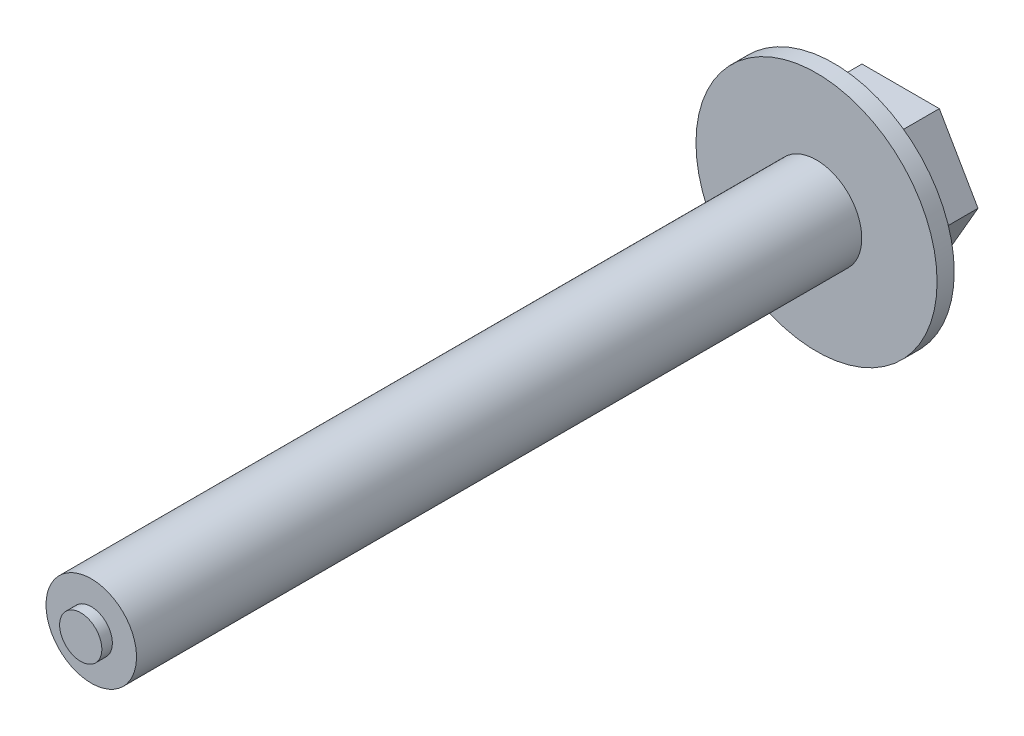
SolidWorks part; units mm, degrees
material "Ti-6Al-4VSolution treated and aged (SS)"
ref_plane "Front Plane" through (0, 0, 0) normal (0, 0, 1) x (1, 0, 0)
ref_plane "Top Plane" through (0, 0, 0) normal (0, 1, 0) x (1, 0, 0)
ref_plane "Right Plane" through (0, 0, 0) normal (1, 0, 0) x (0, 0, -1)
sketch "Sketch1" plane through (0, 0, 0) normal (0, 0, 1) x (1, 0, 0)
  line L1 (3.6662, 0) -> (1.8331, 3.175)
  line L2 (1.8331, 3.175) -> (-1.8331, 3.175)
  line L3 (-1.8331, 3.175) -> (-3.6662, 0)
  line L4 (-3.6662, 0) -> (-1.8331, -3.175)
  line L5 (-1.8331, -3.175) -> (1.8331, -3.175)
  line L6 (1.8331, -3.175) -> (3.6662, 0)
  circle A0 centre (0, 0) radius 3.175 construction
  dimension "D1" = 6.35
extrude "Boss-Extrude1" add sketch "Sketch1" along normal blind 3.175
sketch "Sketch2" plane through (0, 0, 3.175) normal (0, 0, 1) x (1, 0, 0)
  circle A0 centre (0, 0) radius 5.715
  dimension "D1" = 11.43
extrude "Boss-Extrude2" add sketch "Sketch2" along normal blind 0.8128
sketch "Sketch3" plane through (0, 0, 0) normal (1, 0, 0) x (0, 0, -1)
  line L0 (-3.9878, 0) -> (-49.4378, 0)
  line L1 (-3.9878, 5.715) -> (-3.9878, -5.715) construction
  line L2 (2.1933, 0) -> (-2.1933, 0) construction
  line L3 (-3.9878, 0) -> (-3.9878, 2.145)
  line L4 (-3.9878, 2.145) -> (-38.3678, 2.145)
  line L5 (-38.3678, 2.145) -> (-38.3678, 1)
  line L6 (-38.3678, 1) -> (-39.3678, 1)
  line L7 (-39.3678, 1) -> (-39.3678, 2.145)
  line L8 (-39.3678, 2.145) -> (-49.4378, 2.145)
  line L9 (-49.4378, 2.145) -> (-49.4378, 0)
  dimension "D1" = 45.45
  dimension "D2" = 2.145
  dimension "D3" = 1
  dimension "D4" = 34.38
  dimension "D5" = 1
revolve "Revolve1" add sketch "Sketch3" angle 360 about L0
sketch "Sketch4" plane through (0, 0, 0) normal (1, 0, 0) x (0, 0, -1)
  line L0 (6.2865, 0) -> (-6.2865, 0) construction
  line L1 (-49.9378, 3) -> (-38.8678, 3)
  line L2 (-49.9378, 3) -> (-49.9378, -3)
  line L3 (-49.9378, -3) -> (-38.8678, -3)
  line L4 (-38.8678, 3) -> (-38.8678, -3)
  line L5 (-49.9378, 3) -> (-38.8678, -3) construction
  line L6 (-49.9378, -3) -> (-38.8678, 3) construction
  line L7 (-39.3678, 2.145) -> (-49.4378, 2.145) construction
  line L8 (-38.3678, 1) -> (-39.3678, 1) construction
  point P0 (-44.4028, 0)
  point P7 (-44.4028, 2.145)
  point P8 (0, 0)
  point P11 (-38.8678, 1)
  dimension "D1" = 6
extrude "Cut-Extrude1" cut sketch "Sketch4" against normal through all both and the other way through all
equation "\"ShankLength\"= 1.75in'Max of 1.75 in, can be sized down"
equation "\"ThreadLength\"= .078in'Min of 0.078 in, can be sized up"
